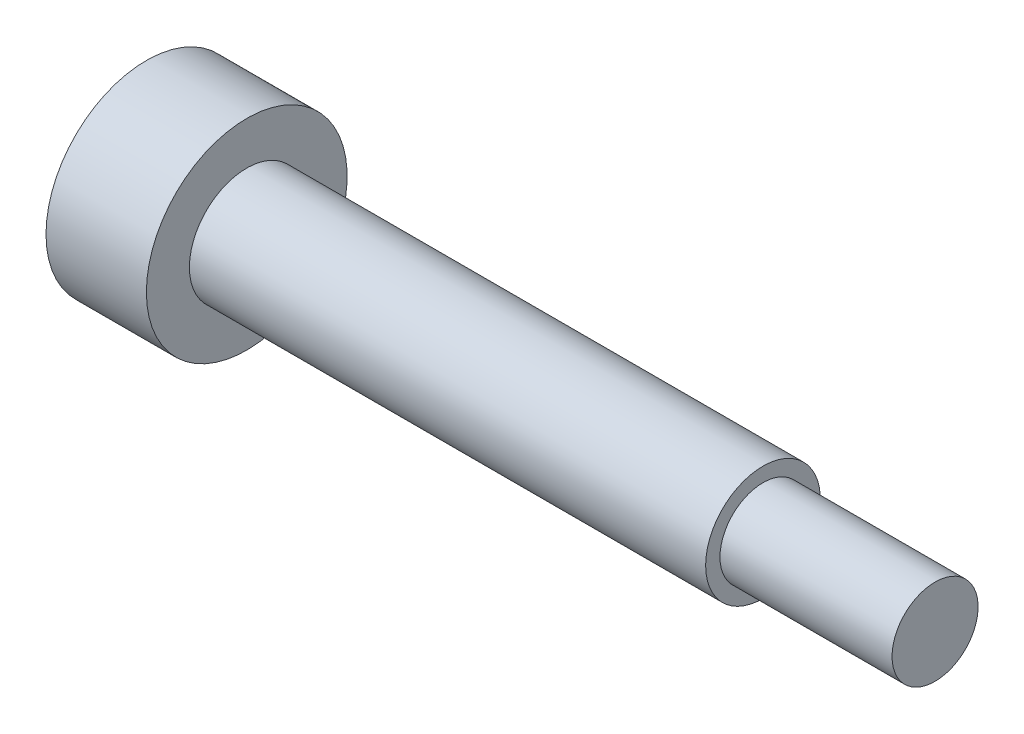
SolidWorks part; units mm, degrees
material "1060 合金"
ref_plane "前视基准面" through (0, 0, 0) normal (0, 0, 1) x (1, 0, 0)
ref_plane "上视基准面" through (0, 0, 0) normal (0, 1, 0) x (1, 0, 0)
ref_plane "右视基准面" through (0, 0, 0) normal (1, 0, 0) x (0, 0, -1)
other "Configuration Table"
sketch "草图1" plane through (0, 0, 0) normal (0, 0, 1) x (1, 0, 0)
  line L0 (0, 0) -> (10456.4321, 0) construction
  line L1 (0, 0) -> (0, 3.5)
  line L2 (0, 3.5) -> (3.5, 3.5)
  line L3 (3.5, 3.5) -> (3.5, 2)
  line L4 (3.5, 2) -> (21.5, 2)
  line L5 (21.5, 2) -> (21.5, 1.5)
  line L6 (21.5, 1.5) -> (27.5, 1.5)
  line L7 (27.5, 1.5) -> (27.5, 0)
  line L8 (27.5, 0) -> (0, 0)
  dimension "D1" = 3.5
  dimension "D2" = 2
  dimension "D3" = 3.5
  dimension "D4" = 18
  dimension "D5" = 1.5
  dimension "D6" = 6
revolve "旋转1" add sketch "草图1" angle 360 about L0
cosmetic thread "装饰螺纹线1" parameters "D1"=8, "D2"=2
sketch "草图2" plane through (0, 0, 0) normal (-1, 0, 0) x (0, 0, 1)
  line L0 (0, 2.8868) -> (0, 0) construction
  line L1 (0, 2.8868) -> (-2.5, 1.4434)
  line L2 (-2.5, 1.4434) -> (-2.5, -1.4434)
  line L3 (-2.5, -1.4434) -> (0, -2.8868)
  line L4 (0, -2.8868) -> (2.5, -1.4434)
  line L5 (2.5, -1.4434) -> (2.5, 1.4434)
  line L6 (2.5, 1.4434) -> (0, 2.8868)
  circle A0 centre (0, 0) radius 2.5 construction
  dimension "D1" = 5
extrude "切除-拉伸1" cut sketch "草图2" against normal blind 3
